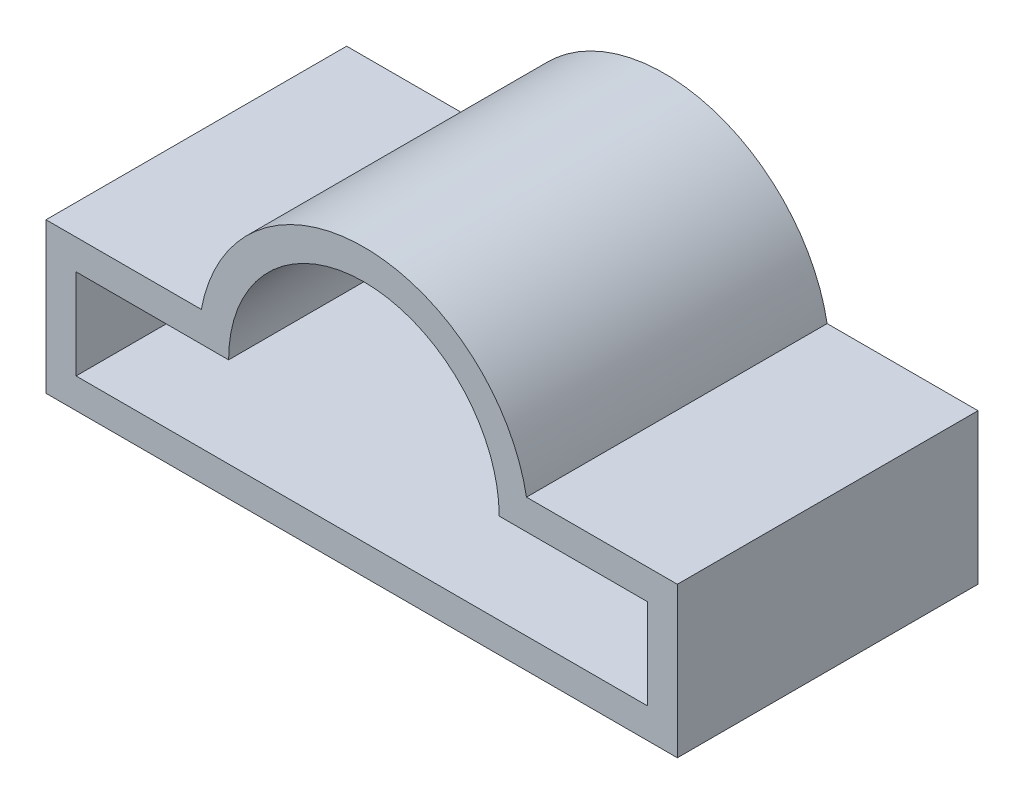
SolidWorks part; units mm, degrees
ref_plane "Front Plane" through (0, 0, 0) normal (0, 0, 1) x (1, 0, 0)
ref_plane "Top Plane" through (0, 0, 0) normal (0, 1, 0) x (1, 0, 0)
ref_plane "Right Plane" through (0, 0, 0) normal (1, 0, 0) x (0, 0, -1)
sketch "Sketch1" plane through (0, 0, 0) normal (0, 0, 1) x (1, 0, 0)
  line L0 (0, 0) -> (0, -100.4744) construction
  line L1 (0, 0) -> (-100.4744, 0) construction
  line L2 (9, 0) -> (18.8524, 0)
  line L3 (18.8524, 0) -> (18.8524, -6)
  line L4 (18.8524, -6) -> (-19.1476, -6)
  line L5 (-19.1476, -6) -> (-19.1476, 0)
  line L6 (-19.1476, 0) -> (-9, 0)
  line L7 (10.8167, 2) -> (20.8524, 2)
  line L8 (20.8524, 2) -> (20.8524, -8)
  line L9 (20.8524, -8) -> (-21.1476, -8)
  line L10 (-21.1476, -8) -> (-21.1476, 2)
  line L11 (-21.1476, 2) -> (-10.8167, 2)
  arc A0 (-9, 0) -> (9, 0) centre (0, 0) ccw construction
  arc A1 (-9, 0) -> (9, 0) centre (0, 0) cw
  arc A2 (-10.8167, 2) -> (10.8167, 2) centre (0, 0) cw
  dimension "D1" = 38
  dimension "D3" = 11
  dimension "D4" = 10
  dimension "D2" = 2
extrude "Boss-Extrude1" add sketch "Sketch1" along normal mid plane 20
